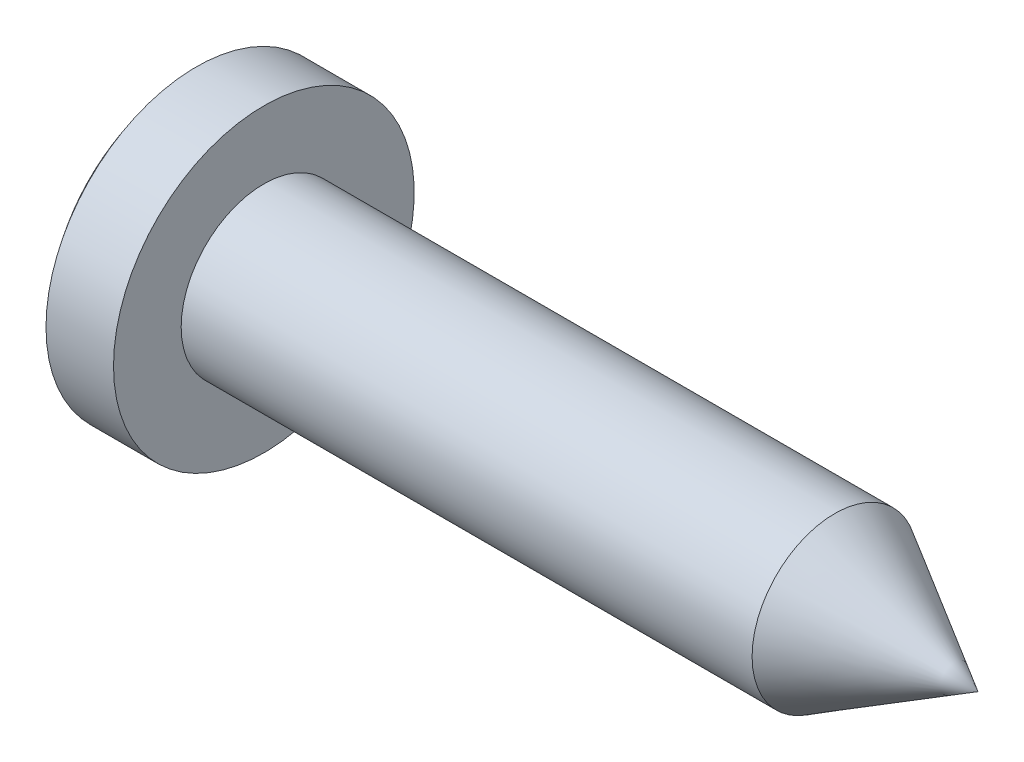
SolidWorks part; units mm, degrees
ref_plane "Front Plane" through (0, 0, 0) normal (0, 0, 1) x (1, 0, 0)
ref_plane "Top Plane" through (0, 0, 0) normal (0, 1, 0) x (1, 0, 0)
ref_plane "Right Plane" through (0, 0, 0) normal (1, 0, 0) x (0, 0, -1)
other "Configuration Table"
sketch "Sketch1" plane through (0, 0, 0) normal (0, 0, 1) x (1, 0, 0)
  line L0 (0, 0) -> (5.2282, 0) construction
  line L2 (0, 2) -> (-0.898, 2)
  line L3 (-1.6, 0) -> (-1.6, -0.7496) construction
  line L4 (-1.6, 0) -> (9.5, 0)
  line L5 (0, 1.1) -> (9.5, 1.1)
  line L6 (9.5, 1.1) -> (9.5, 0)
  line L7 (0, 1.1) -> (0, 2)
  arc A0 (-0.898, 2) -> (-1.6, 0) centre (1.6, 0) ccw
  dimension "rf" = 3.2
  dimension "Dk" = 4
  dimension "K" = 1.6
  dimension "d" = 2.2
  dimension "l" = 9.5
revolve "Revolve1" add sketch "Sketch1" angle 360 about L0
cosmetic thread "ThreadCosmetic" [suppressed] parameters "D1"=9.28, "D2"=1.63
chamfer "Chamfer1" distance 0.22 angle 60 1 edges at (9.5, 0, 1.1)
sketch "Sketch5" plane through (0, 0, 0) normal (0, 0, 1) x (1, 0, 0)
  line L0 (0.7155, 0.815) -> (0.2445, 0.815)
  line L1 (0.2445, 0.815) -> (0.08, 1.1)
  line L2 (0.7155, 0.815) -> (0.88, 1.1)
  line L3 (0.08, 1.1) -> (0.08, 1.35)
  line L4 (0.88, 1.1) -> (0.88, 1.35)
  line L5 (0.08, 1.35) -> (0.88, 1.35)
  line L6 (0.48, 0.815) -> (0.48, 0) construction
  line L7 (0, 0) -> (7.3035, 0) construction
  line L9 (9.1189, 1.1) -> (0, 1.1) construction
  line L12 (0, -1.1) -> (0, 1.1) construction
  dimension "D2" = 60
  dimension "D3" = 0.25
  dimension "advance" = 0.8
  dimension "minordia" = 1.63
  dimension "threadstart" = 0.48
revolve "ThreadSchematic" [suppressed] cut sketch "Sketch5" angle 360 about L7
pattern_linear "ThdSchPat" [suppressed] count 12 spacing 0.8 along (1, 0, 0)
sketch "Sketch2" plane through (0, 0, 0) normal (0, 0, 1) x (1, 0, 0)
  line L0 (0, 0) -> (5.7679, 0) construction
  line L1 (9.5, 0) -> (7.5947, 1.1)
  line L3 (9.5, 1.1) -> (9.5, 0) construction
  line L4 (7.5947, 1.1) -> (7.5947, 1.2)
  line L5 (7.5947, 1.2) -> (9.6, 1.2)
  line L6 (9.6, 1.2) -> (9.6, 0)
  line L7 (9.6, 0) -> (9.5, 0)
  point P9 (0, 1.1)
  dimension "D1" = 30
  dimension "D2" = 0.1
  dimension "D3" = 0.1
revolve "EndCone" cut sketch "Sketch2" angle 360 about L0
ref_plane "Plane4" through (-1.6, 0, 0) normal (1, 0, 0) x (0, 0, -1)
sketch "Sketch3" plane through (-1.6, 0, 0) normal (1, 0, 0) x (0, 0, -1)
  line L0 (0, 2.343) -> (0, -2.4842) construction
  line L1 (2.7661, 0) -> (-3.4558, 0) construction
  line L2 (-0.2375, 0.95) -> (0.2375, 0.95)
  line L3 (0.2375, 0.95) -> (0.1425, 0.57)
  line L4 (0, 0) -> (1.9578, 1.9578) construction
  line L5 (0.1425, 0.57) -> (0.299, 0.299)
  line L6 (0.1425, 0.57) -> (0, 0) construction
  line L7 (-0.1425, 0.57) -> (-0.299, 0.299)
  line L8 (-0.2375, 0.95) -> (-0.1425, 0.57)
  line L9 (0.95, 0.2375) -> (0.95, -0.2375)
  line L10 (0.95, -0.2375) -> (0.57, -0.1425)
  line L11 (0.57, -0.1425) -> (0.299, -0.299)
  line L12 (0.57, 0.1425) -> (0.299, 0.299)
  line L13 (0.95, 0.2375) -> (0.57, 0.1425)
  line L14 (0.2375, -0.95) -> (-0.2375, -0.95)
  line L15 (-0.2375, -0.95) -> (-0.1425, -0.57)
  line L16 (-0.1425, -0.57) -> (-0.299, -0.299)
  line L17 (0.1425, -0.57) -> (0.299, -0.299)
  line L18 (0.2375, -0.95) -> (0.1425, -0.57)
  line L19 (-0.95, -0.2375) -> (-0.95, 0.2375)
  line L20 (-0.95, 0.2375) -> (-0.57, 0.1425)
  line L21 (-0.57, 0.1425) -> (-0.299, 0.299)
  line L22 (-0.57, -0.1425) -> (-0.299, -0.299)
  line L23 (-0.95, -0.2375) -> (-0.57, -0.1425)
  point P14 (0, 0.95)
  point P23 (0.95, 0)
  point P30 (0, -0.95)
  point P37 (-0.95, 0)
  dimension "D1" = 45
  dimension "m" = 1.9
  dimension "D3" = 0.475
  dimension "D4" = 75
  dimension "D5" = 1.14
extrude "Cut-Extrude1" cut sketch "Sketch3" along normal blind 0.85 draft 6
sketch "Sketch4" plane through (-1.6, 0, 0) normal (1, 0, 0) x (0, 0, -1)
  line L0 (0, 2.1951) -> (0, -2.1951) construction
  line L1 (2.1996, 0) -> (-2.3835, 0) construction
  line L2 (-0.8397, -0.8397) -> (0.8397, 0.8397) construction
  line L3 (0.95, 0.2375) -> (-0.95, 0.2375)
  line L4 (0.95, 0.2375) -> (0.95, -0.2375)
  line L5 (0.95, -0.2375) -> (-0.95, -0.2375)
  line L6 (-0.95, 0.2375) -> (-0.95, -0.2375)
  line L7 (0.2375, 0.95) -> (-0.2375, 0.95)
  line L8 (0.2375, 0.95) -> (0.2375, -0.95)
  line L9 (0.2375, -0.95) -> (-0.2375, -0.95)
  line L10 (-0.2375, 0.95) -> (-0.2375, -0.95)
  line L11 (0.8397, 0.8397) -> (0.3859, 0.2375)
  line L12 (0.8397, 0.8397) -> (0.2375, 0.3859)
  line L13 (0.2375, 0.3859) -> (-0.2375, 0.3859) construction
  line L14 (0, 0) -> (-0.8397, 0.8397) construction
  line L15 (-0.8397, -0.8397) -> (-0.2375, -0.3859)
  line L16 (-0.8397, -0.8397) -> (-0.3859, -0.2375)
  line L17 (-0.2375, 0.3859) -> (-0.8397, 0.8397)
  line L18 (-0.8397, 0.8397) -> (-0.3859, 0.2375)
  line L19 (-0.3859, -0.2375) -> (-0.3859, 0.2375) construction
  line L20 (0.3859, -0.2375) -> (0.8397, -0.8397)
  line L21 (0.8397, -0.8397) -> (0.2375, -0.3859)
  circle A0 centre (0, 0) radius 1.1875 construction
  dimension "m" = 1.9
  dimension "D1" = 2.375
  dimension "D2" = 0.475
  dimension "D3" = 45
  dimension "D4" = 8
  dimension "D5" = 45
extrude "TypeZ" [suppressed] cut sketch "Sketch4" along normal blind 0.8
equation "\"D1@Chamfer1\" = \"d@Sketch1\"/10"
equation "\"D1@ThreadCosmetic\" = \"l@Sketch1\" - \"D1@Chamfer1\""
equation "\"minordia@Sketch5\" = \"D2@ThreadCosmetic\""
equation "\"D1@Plane4\" = \"K@Sketch1\""
equation "\"D5@Sketch3\" = \"m@Sketch3\" * 3 / 5"
equation "\"D3@Sketch3\" = \"m@Sketch3\" / 4"
equation "\"D2@Sketch4\" =  \"m@Sketch4\" / 4"
equation "\"D1@TypeZ\" = \"K@Sketch1\" / 2"
equation "\"D1@Sketch4\" = \"m@Sketch4\" * 5 / 4"
equation "\"m@Sketch4\" = \"m@Sketch3\""
equation "\"threadstart@Sketch5\" = \"advance@Sketch5\"*0.6"
equation "\"D1@ThdSchPat\" = int((\"l@Sketch1\"/\"advance@Sketch5\") + 0.999)"
equation "\"D3@ThdSchPat\" = \"advance@Sketch5\""
